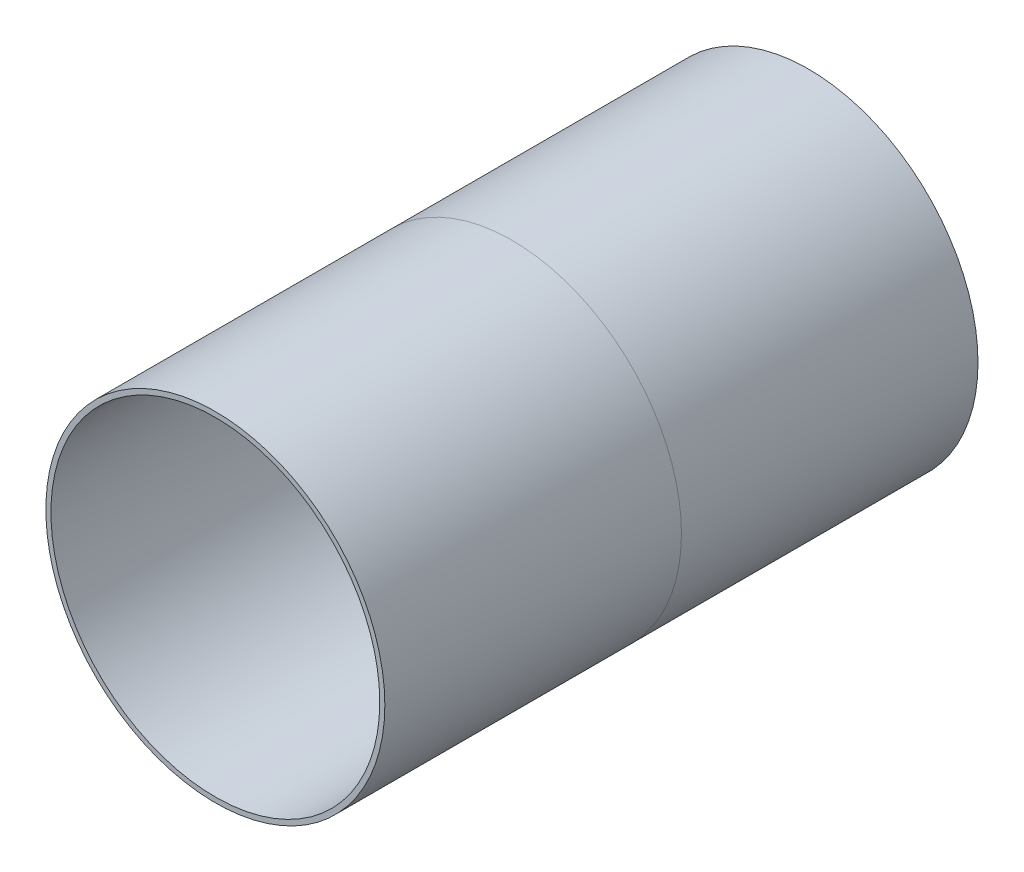
SolidWorks part; units mm, degrees
ref_plane "Plan de face" through (0, 0, 0) normal (0, 0, 1) x (1, 0, 0)
ref_plane "Plan de dessus" through (0, 0, 0) normal (0, 1, 0) x (1, 0, 0)
ref_plane "Plan de droite" through (0, 0, 0) normal (1, 0, 0) x (0, 0, -1)
sketch "Esquisse2" plane through (0, 0, 0) normal (0, 0, 1) x (1, 0, 0)
  circle A0 centre (0, 0) radius 76.1746
  circle A1 centre (0, 0) radius 73.914
  dimension "D1" = 152.3492
  dimension "D2" = 147.828
extrude "Boss.-Extru.1" add sketch "Esquisse2" along normal blind 133.35
sketch "Esquisse3" plane through (0, 0, 133.35) normal (0, 0, 1) x (1, 0, 0)
  circle A0 centre (0, 0) radius 76.2
  circle A1 centre (0, 0) radius 73.914
  dimension "D1" = 147.828
extrude "Boss.-Extru.2" add sketch "Esquisse3" along normal blind 133.35
